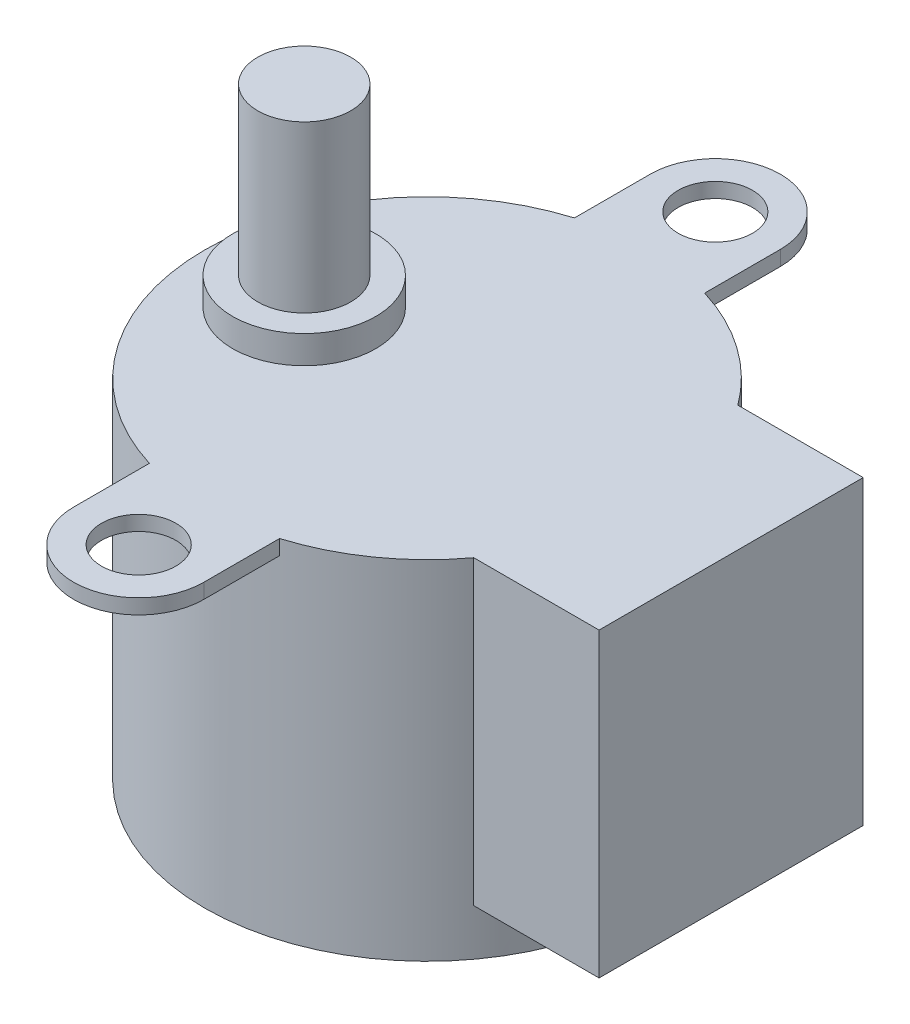
SolidWorks part; units mm, degrees
ref_plane "前视基准面" through (0, 0, 0) normal (0, 0, 1) x (1, 0, 0)
ref_plane "上视基准面" through (0, 0, 0) normal (0, 1, 0) x (1, 0, 0)
ref_plane "右视基准面" through (0, 0, 0) normal (1, 0, 0) x (0, 0, -1)
sketch "草图1" plane through (0, 0, 0) normal (0, 1, 0) x (1, 0, 0)
  circle A0 centre (0, 0) radius 11.95
  dimension "D1" = 23.9
extrude "凸台-拉伸1" add sketch "草图1" along normal blind 18.7
sketch "草图2" plane through (0, 18.7, 0) normal (0, 1, 0) x (1, 0, 0)
  line L0 (-11.95, 0) -> (16.35, 0) construction
  line L1 (16.35, -7.1) -> (16.35, 7.1)
  line L2 (16.35, 7.1) -> (9.6121, 7.1)
  line L3 (16.35, -7.1) -> (9.6121, -7.1)
  circle A0 centre (0, 0) radius 11.95 construction
  arc A1 (9.6121, 7.1) -> (9.6121, -7.1) centre (0, 0) cw
  point P9 (16.35, 0)
  circle M3 centre (0, 0) radius 11.95
  dimension "D1" = 28.3
  dimension "D2" = 14.2
extrude "凸台-拉伸8" add sketch "草图2" against normal blind 16.2 contours A1 L0 L1 L2 | L0 L3 L1 M3
sketch "草图3" plane through (0, 18.7, 0) normal (0, 1, 0) x (1, 0, 0)
  line L0 (-3.5, 15.5) -> (-3.5, 11.426)
  line L1 (3.5, 15.5) -> (3.5, 11.426)
  line L2 (-3.5, -15.5) -> (-3.5, -11.426)
  line L3 (3.5, -15.5) -> (3.5, -11.426)
  line L4 (0, -15.5) -> (0, 15.5) construction
  circle A0 centre (0, 15.5) radius 2
  arc A1 (9.6121, 7.1) -> (9.6121, -7.1) centre (0, 0) ccw construction
  arc A2 (3.5, 15.5) -> (-3.5, 15.5) centre (0, 15.5) ccw
  circle A3 centre (0, -15.5) radius 2
  arc A4 (-3.5, -15.5) -> (3.5, -15.5) centre (0, -15.5) ccw
  arc A5 (-3.5, 11.426) -> (3.5, 11.426) centre (0, 0) cw
  arc A6 (-3.5, -11.426) -> (3.5, -11.426) centre (0, 0) ccw
  point P21 (0, 0)
  dimension "D1" = 4
  dimension "D2" = 7
  dimension "D3" = 31
extrude "凸台-拉伸9" add sketch "草图3" against normal blind 0.8
sketch "草图4" plane through (0, 18.7, 0) normal (0, 1, 0) x (1, 0, 0)
  circle A0 centre (-6.6, 0) radius 3.85
  dimension "D1" = 7.7
  dimension "D2" = 6.6
extrude "凸台-拉伸10" add sketch "草图4" along normal blind 1.5
sketch "草图5" plane through (0, 20.2, 0) normal (0, 1, 0) x (1, 0, 0)
  circle A0 centre (-6.6, 0) radius 2.5
  dimension "D1" = 5
extrude "凸台-拉伸11" add sketch "草图5" along normal blind 8.9
